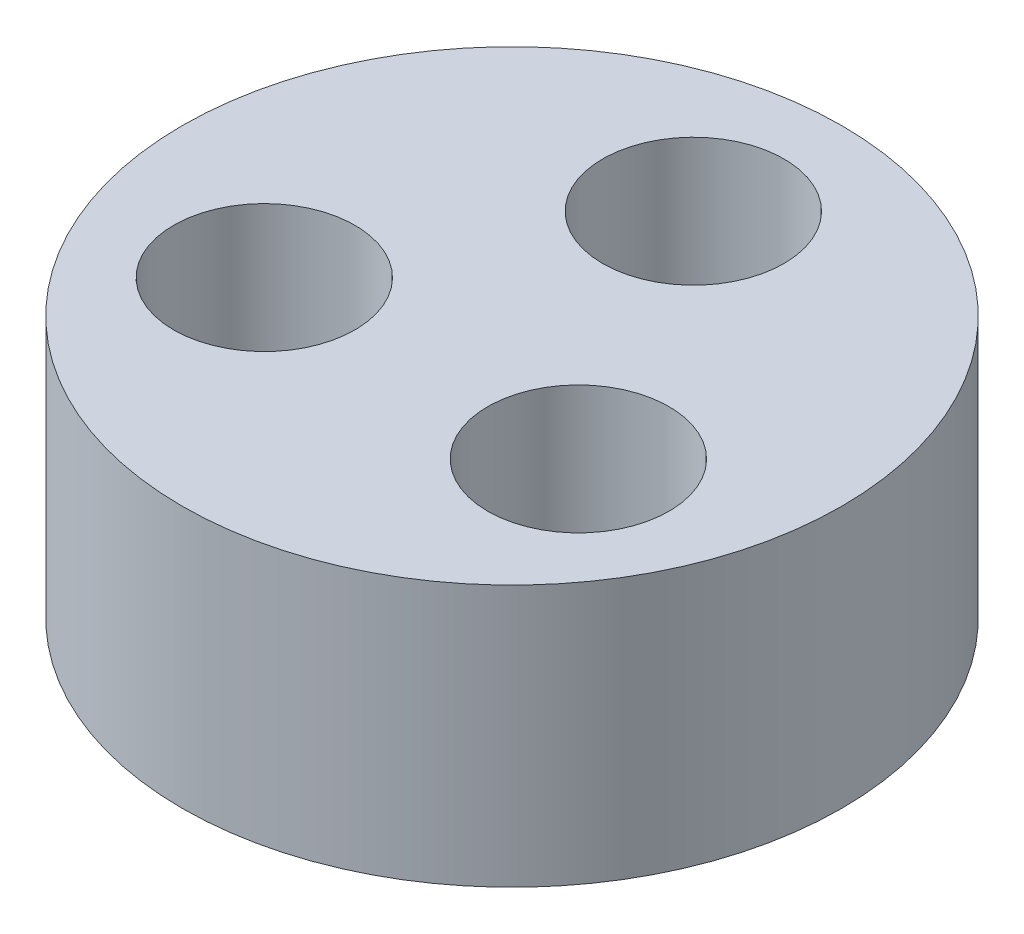
SolidWorks part; units mm, degrees
ref_plane "Front Plane" through (0, 0, 0) normal (0, 0, 1) x (1, 0, 0)
ref_plane "Top Plane" through (0, 0, 0) normal (0, 1, 0) x (1, 0, 0)
ref_plane "Right Plane" through (0, 0, 0) normal (1, 0, 0) x (0, 0, -1)
sketch "Sketch1" plane through (0, 0, 0) normal (0, 1, 0) x (1, 0, 0)
  line L1 (1.9053, -1.1) -> (0, 2.2) construction
  line L2 (0, 2.2) -> (-1.9053, -1.1) construction
  line L3 (-1.9053, -1.1) -> (1.9053, -1.1) construction
  circle A0 centre (0, 0) radius 4
  circle A1 centre (0, 0) radius 1.1 construction
  circle A2 centre (0, 2.2) radius 1.1
  circle A3 centre (1.9053, -1.1) radius 1.1
  circle A4 centre (-1.9053, -1.1) radius 1.1
  dimension "D1" = 8
  dimension "D2" = 2.2
  dimension "D3" = 2.2
extrude "Boss-Extrude1" add sketch "Sketch1" along normal blind 3.175
